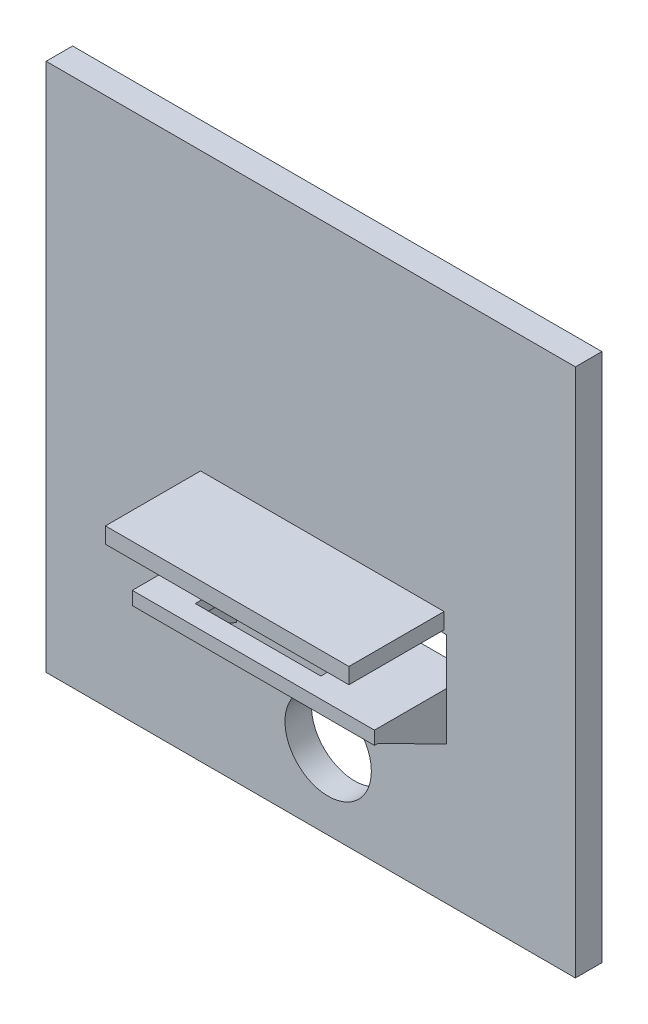
SolidWorks part; units mm, degrees
ref_plane "Front Plane" through (0, 0, 0) normal (0, 0, 1) x (1, 0, 0)
ref_plane "Top Plane" through (0, 0, 0) normal (0, 1, 0) x (1, 0, 0)
ref_plane "Right Plane" through (0, 0, 0) normal (1, 0, 0) x (0, 0, -1)
sketch "Sketch1" plane through (0, 0, 0) normal (0, 0, 1) x (1, 0, 0)
  line L1 (0, 76.2376) -> (200, 76.2376)
  line L2 (0, 76.2376) -> (0, -123.7624)
  line L3 (0, -123.7624) -> (200, -123.7624)
  line L4 (200, 76.2376) -> (200, -123.7624)
  line L5 (59.8073, -35.7695) -> (151.3073, -35.7695)
  line L6 (59.8073, -35.7695) -> (59.8073, -53.3695)
  line L7 (59.8073, -53.3695) -> (151.3073, -53.3695)
  line L8 (151.3073, -35.7695) -> (151.3073, -53.3695)
  circle A0 centre (106.5699, -94.6722) radius 16.3178
  point P10 (107.4761, -100.1094)
  point P11 (0, 0)
  point P12 (0, 0)
  point P13 (0, 0)
  point P14 (0, 0)
  dimension "D1" = 200
  dimension "D2" = 200
  dimension "D3" = 91.5
  dimension "D4" = 17.6
extrude "Boss-Extrude1" add sketch "Sketch1" along normal blind 10
ref_plane "Plane1" through (0, -53.3695, 0) normal (0, -1, 0) x (1, 0, 0)
sketch "Sketch2" plane through (0, -53.3695, 0) normal (0, -1, 0) x (1, 0, 0)
  line L1 (59.8073, 10) -> (151.3073, 10)
  line L2 (59.8073, 10) -> (59.8073, 37.2443)
  line L3 (59.8073, 37.2443) -> (151.3073, 37.2443)
  line L4 (151.3073, 10) -> (151.3073, 37.2443)
  line L5 (76.0263, 29.6781) -> (123.4906, 29.6781)
  line L6 (76.0263, 29.6781) -> (76.0263, 14.8446)
  line L7 (76.0263, 14.8446) -> (123.4906, 14.8446)
  line L8 (123.4906, 29.6781) -> (123.4906, 14.8446)
extrude "Boss-Extrude2" add sketch "Sketch2" along normal blind 5
ref_plane "Plane4" through (59.8073, 0, 0) normal (-1, 0, 0) x (0, 0, 1)
sketch "Sketch5" plane through (59.8073, 0, 0) normal (-1, 0, 0) x (0, 0, 1)
  line L0 (37.2443, -58.3695) -> (10, -71.5706)
  line L1 (37.2443, -58.3695) -> (37.2443, -53.3695) construction
  line L2 (37.2443, -58.3695) -> (10, -58.3695) construction
  line L3 (10, 76.2376) -> (10, -123.7624) construction
  line L4 (10, -71.5706) -> (10, -58.3695)
  line L5 (10, -58.3695) -> (37.2443, -58.3695)
extrude "Boss-Extrude3" add sketch "Sketch5" against normal blind 12.0382
ref_plane "Plane5" through (151.3073, 0, 0) normal (1, 0, 0) x (0, 0, -1)
sketch "Sketch6" plane through (151.3073, 0, 0) normal (1, 0, 0) x (0, 0, -1)
  line L0 (-37.2443, -57.6775) -> (-10, -71.5706)
  line L1 (-37.2443, -58.3695) -> (-37.2443, -53.3695) construction
  line L2 (-10, -58.3695) -> (-10, -71.5706) construction
  line L3 (-10, -71.5706) -> (-37.2443, -58.3695) construction
  line L4 (-10, -71.5706) -> (-10, -58.3695)
  line L5 (-10, -123.7624) -> (-10, 76.2376) construction
  line L6 (-10, -58.3695) -> (-37.2443, -57.6775)
extrude "Boss-Extrude4" add sketch "Sketch6" against normal blind 12
ref_plane "Plane6" through (0, -33.3695, 0) normal (0, 1, 0) x (1, 0, 0)
sketch "Sketch8" plane through (0, -33.3695, 0) normal (0, 1, 0) x (1, 0, 0)
  line L1 (151.6405, -11.2694) -> (59.6403, -11.2694)
  line L2 (151.6405, -11.2694) -> (151.6405, -47.2329)
  line L3 (151.6405, -47.2329) -> (59.6403, -47.2329)
  line L4 (59.6403, -11.2694) -> (59.6403, -47.2329)
extrude "Boss-Extrude10" add sketch "Sketch8" along normal blind 6 separate body
